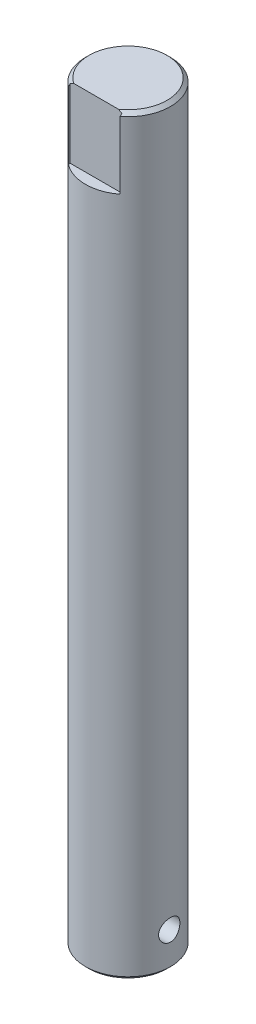
SolidWorks part; units mm, degrees
ref_plane "Front Plane" through (0, 0, 0) normal (0, 0, 1) x (1, 0, 0)
ref_plane "Top Plane" through (0, 0, 0) normal (0, 1, 0) x (1, 0, 0)
ref_plane "Right Plane" through (0, 0, 0) normal (1, 0, 0) x (0, 0, -1)
sketch "Sketch1" plane through (0, 0, 0) normal (0, 1, 0) x (1, 0, 0)
  circle A0 centre (0, 0) radius 6
extrude "Boss-Extrude1" add sketch "Sketch1" along normal blind 106
chamfer "Chamfer1" distance 0.5 angle 45 2 edges at (0, 0, 6) (0, 106, 6)
sketch "Sketch2" plane through (0, 0, 0) normal (1, 0, 0) x (0, 0, -1)
  circle A0 centre (0, 5) radius 1.5
  dimension "D1" = 5
extrude "Cut-Extrude1" cut sketch "Sketch2" against normal through all both and the other way through all
sketch "Sketch3" plane through (0, 0, 0) normal (0, 0, 1) x (1, 0, 0)
  point P0 (0, 105.3813)
ref_plane "Plane1" through (0, 0, 4.5) normal (0, 0, 1) x (1, 0, 0)
sketch "Sketch4" plane through (0, 0, 4.5) normal (0, 0, 1) x (1, 0, 0)
  line L0 (5.5, 106) -> (-5.5, 106) construction
  line L1 (-3.6514, 112.5973) -> (3.6514, 112.5973)
  line L2 (-3.6514, 112.5973) -> (-3.6514, 96)
  line L3 (-3.6514, 96) -> (3.6514, 96)
  line L4 (3.6514, 112.5973) -> (3.6514, 96)
  line L5 (-3.6514, 112.5973) -> (3.6514, 96) construction
  line L6 (-3.6514, 96) -> (3.6514, 112.5973) construction
  point P0 (0, 104.2986)
  dimension "D1" = 10
extrude "Cut-Extrude2" cut sketch "Sketch4" along normal through all
